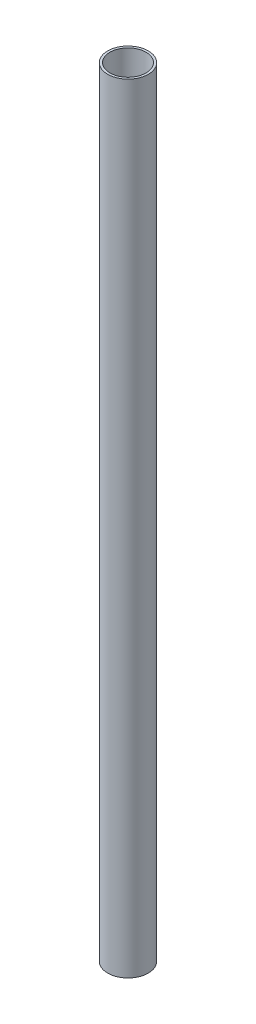
SolidWorks part; units mm, degrees
material "AISI 1020"
ref_plane "Front Plane" through (0, 0, 0) normal (0, 0, 1) x (1, 0, 0)
ref_plane "Top Plane" through (0, 0, 0) normal (0, 1, 0) x (1, 0, 0)
ref_plane "Right Plane" through (0, 0, 0) normal (1, 0, 0) x (0, 0, -1)
sketch "Sketch1" plane through (0, 0, 0) normal (0, 1, 0) x (1, 0, 0)
  circle A0 centre (13.6327, 6.0794) radius 7.0485
  circle A1 centre (13.6327, 6.0794) radius 7.9375
  dimension "D1" = 14.097
  dimension "D2" = 15.875
extrude "Boss-Extrude1" add sketch "Sketch1" along normal blind 304.41
